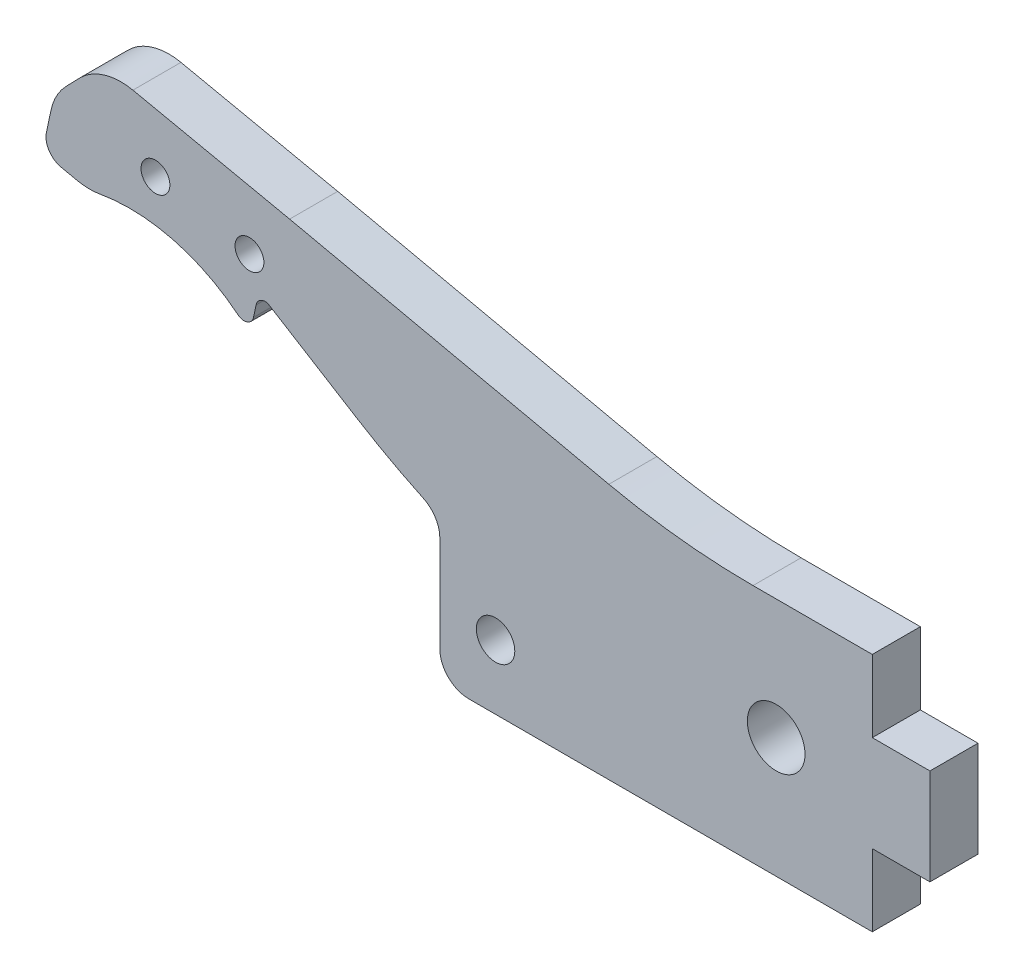
SolidWorks part; units mm, degrees
ref_plane "Front Plane" through (0, 0, 0) normal (0, 0, 1) x (1, 0, 0)
ref_plane "Top Plane" through (0, 0, 0) normal (0, 1, 0) x (1, 0, 0)
ref_plane "Right Plane" through (0, 0, 0) normal (1, 0, 0) x (0, 0, -1)
sketch "Sketch1" plane through (0, 0, 0) normal (0, 0, 1) x (1, 0, 0)
  line L0 (0, 39.5382) -> (0, -44.4482) construction
  line L1 (-59.7321, 0) -> (104.5892, 0) construction
  line L2 (7.5898, 12.5) -> (20, 12.5)
  line L3 (20, 12.5) -> (20, 5)
  line L4 (0, -12.5) -> (20, -12.5)
  line L8 (20, 5) -> (26, 5)
  line L9 (26, 5) -> (26, -5)
  line L10 (20, -5) -> (26, -5)
  line L11 (20, -5) -> (20, -12.5)
  line L20 (0, -12.5) -> (-22, -12.5)
  line L21 (-25, -9.5) -> (-25, 0.5)
  line L29 (-40.6281, 21.415) -> (-56.9379, 24.8818)
  line L30 (-62.5014, 23.1808) -> (-63.9107, 21.7215)
  line L31 (-65.4635, 18.801) -> (-65.9375, 16.5713)
  line L32 (-64.397, 14.1992) -> (-62.6897, 13.8363)
  line L33 (-44.1206, 11.934) -> (-44.3886, 10.6735)
  line L34 (-42.9346, 12.7042) -> (-33.5197, 6.9018)
  line L35 (-40.6281, 21.415) -> (-7.4134, 14.1267)
  circle A0 centre (10, 0) radius 3
  circle A14 centre (-19.2, -5.8) radius 2
  arc A24 (-22, -12.5) -> (-25, -9.5) centre (-22, -9.5) cw
  arc A25 (-25, 0.5) -> (-26.7175, 3.2121) centre (-28, 0.5) ccw
  arc A28 (-60.3988, 13.7966) -> (-45.9931, 10.1019) centre (-57.2684, -3.9291) cw
  arc A29 (-63.9107, 21.7215) -> (-65.4635, 18.801) centre (-59.5946, 17.5535) ccw
  arc A30 (-56.9379, 24.8818) -> (-62.5014, 23.1808) centre (-58.1853, 19.0129) ccw
  arc A31 (-62.6897, 13.8363) -> (-60.3988, 13.7966) centre (-61.4423, 19.7052) ccw
  arc A32 (-65.9375, 16.5713) -> (-64.397, 14.1992) centre (-63.9812, 16.1555) ccw
  arc A33 (-42.9346, 12.7042) -> (-44.1206, 11.934) centre (-43.1425, 11.7261) ccw
  arc A34 (-44.3886, 10.6735) -> (-45.9931, 10.1019) centre (-45.3667, 10.8814) cw
  circle A35 centre (-54.5907, 18.2488) radius 1.5
  circle A36 centre (-44.8092, 16.1697) radius 1.5
  arc A37 (7.5898, 12.5) -> (-7.4134, 14.1267) centre (7.5898, 82.5) cw
  arc A38 (-33.5197, 6.9018) -> (-26.7175, 3.2121) centre (3.2068, 66.4935) ccw
  point P13 (30.9161, 0)
  point P17 (0, 12)
  point P20 (0, 12.5)
  point P25 (26, 0)
  point P35 (-64.1927, 12.5)
  point P38 (-62.9419, 0.5)
  dimension "D1" = 6
  dimension "D2" = 0
  dimension "D4" = 10
  dimension "D5" = 25
  dimension "D6" = 4
  dimension "D7" = 39.2
  dimension "D8" = 6
  dimension "D9" = 5
  dimension "D11" = 25
  dimension "D12" = 70
  dimension "D10" = 18.3
  dimension "D25" = 3
  dimension "D13" = 70
  dimension "D3" = 20
extrude "Boss-Extrude1" add sketch "Sketch1" along normal blind 5
